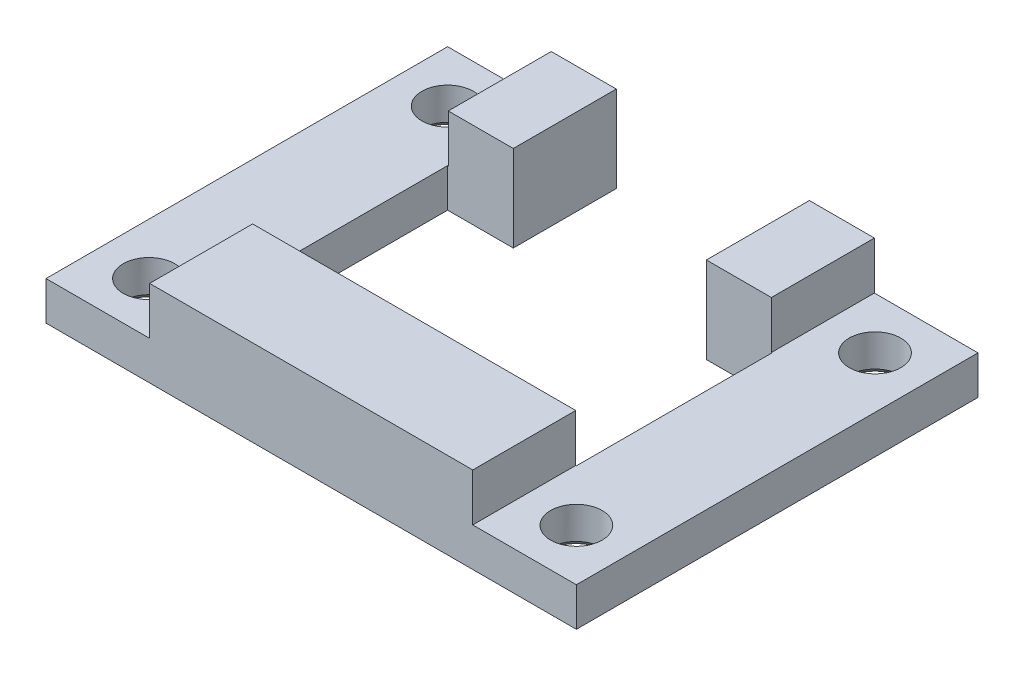
SolidWorks part; units mm, degrees
ref_plane "Front Plane" through (0, 0, 0) normal (0, 0, 1) x (1, 0, 0)
ref_plane "Top Plane" through (0, 0, 0) normal (0, 1, 0) x (1, 0, 0)
ref_plane "Right Plane" through (0, 0, 0) normal (1, 0, 0) x (0, 0, -1)
sketch "Sketch1" plane through (0, 0, 0) normal (0, 1, 0) x (1, 0, 0)
  line L1 (-20.6, -15.6) -> (20.6, -15.6)
  line L2 (-20.6, -15.6) -> (-20.6, 15.6)
  line L3 (-20.6, 15.6) -> (20.6, 15.6)
  line L4 (20.6, -15.6) -> (20.6, 15.6)
  line L5 (-20.6, -15.6) -> (20.6, 15.6) construction
  line L6 (-20.6, 15.6) -> (20.6, -15.6) construction
  point P0 (0, 0)
  dimension "D1" = 31.2
  dimension "D2" = 41.2
extrude "Boss-Extrude1" add sketch "Sketch1" along normal blind 3
sketch "Sketch2" plane through (0, 3, 0) normal (0, 1, 0) x (1, 0, 0)
  line L0 (20.6, 15.6) -> (-20.6, 15.6) construction
  line L1 (12.55, 15.6) -> (-12.55, 15.6)
  line L2 (12.55, 15.6) -> (12.55, -15.6)
  line L3 (12.55, -15.6) -> (-12.55, -15.6)
  line L4 (-12.55, 15.6) -> (-12.55, -15.6)
  line L5 (-20.6, -15.6) -> (20.6, -15.6) construction
  line L6 (20.6, -15.6) -> (20.6, 15.6) construction
  line L7 (-20.6, 15.6) -> (-20.6, -15.6) construction
  dimension "D1" = 8.05
  dimension "D2" = 8.05
extrude "Boss-Extrude2" add sketch "Sketch2" along normal blind 3.7
sketch "Sketch3" plane through (0, 3, 0) normal (0, 1, 0) x (1, 0, 0)
  line L1 (20.6, -15.6) -> (20.6, 15.6) construction
  line L2 (-20.6, 15.6) -> (-20.6, -15.6) construction
  line L4 (12.55, -15.6) -> (20.6, -15.6) construction
  line L5 (20.6, 15.6) -> (12.55, 15.6) construction
  circle A0 centre (16.6, -11.6) radius 2
  circle A1 centre (-16.6, -11.6) radius 2
  circle A2 centre (16.6, 11.6) radius 2
  circle A3 centre (-16.6, 11.6) radius 2
  point P4 (0, 0)
  point P5 (0, 0)
  point P16 (0, 0)
  dimension "D1" = 4
  dimension "D2" = 4
  dimension "D3" = 4
  dimension "D4" = 4
  dimension "D5" = 4
extrude "Cut-Extrude1" cut sketch "Sketch3" against normal up to surface (3 mm away) up to face at (0, 0, 0)
sketch "Sketch4" plane through (0, 0, 0) normal (0, -1, 0) x (1, 0, 0)
  line L0 (20.6, -15.6) -> (-20.6, -15.6) construction
  line L1 (-7.5, -15.6) -> (7.5, -15.6)
  line L2 (-7.5, -15.6) -> (-7.5, -7.6)
  line L4 (7.5, -15.6) -> (7.5, -7.6)
  line L7 (-20.6, -15.6) -> (-20.6, 15.6) construction
  line L8 (-12.6, 7.6) -> (12.6, 7.6)
  line L9 (-12.6, 7.6) -> (-12.6, -7.6)
  line L10 (-12.6, -7.6) -> (-7.5, -7.6)
  line L11 (12.6, 7.6) -> (12.6, -7.6)
  line L12 (20.6, 15.6) -> (20.6, -15.6) construction
  line L13 (7.5, -7.6) -> (12.6, -7.6)
  line L14 (-20.6, 15.6) -> (20.6, 15.6) construction
  point P8 (0, -15.6)
  point P9 (0, -15.6)
  point P20 (-7.0757, 7.6)
  point P21 (0, 0)
  dimension "D1" = 8
  dimension "D2" = 15
  dimension "D3" = 8
  dimension "D4" = 8
  dimension "D5" = 8
extrude "Cut-Extrude2" cut sketch "Sketch4" against normal up to surface (6.7 mm away) up to face at (0, 6.7, 0)
chamfer "Chamfer1" distance 0.5 angle 45 4 edges at (-16.6, 0, -13.6) (16.6, 0, -13.6) (16.6, 0, 9.6) (-16.6, 0, 9.6)
